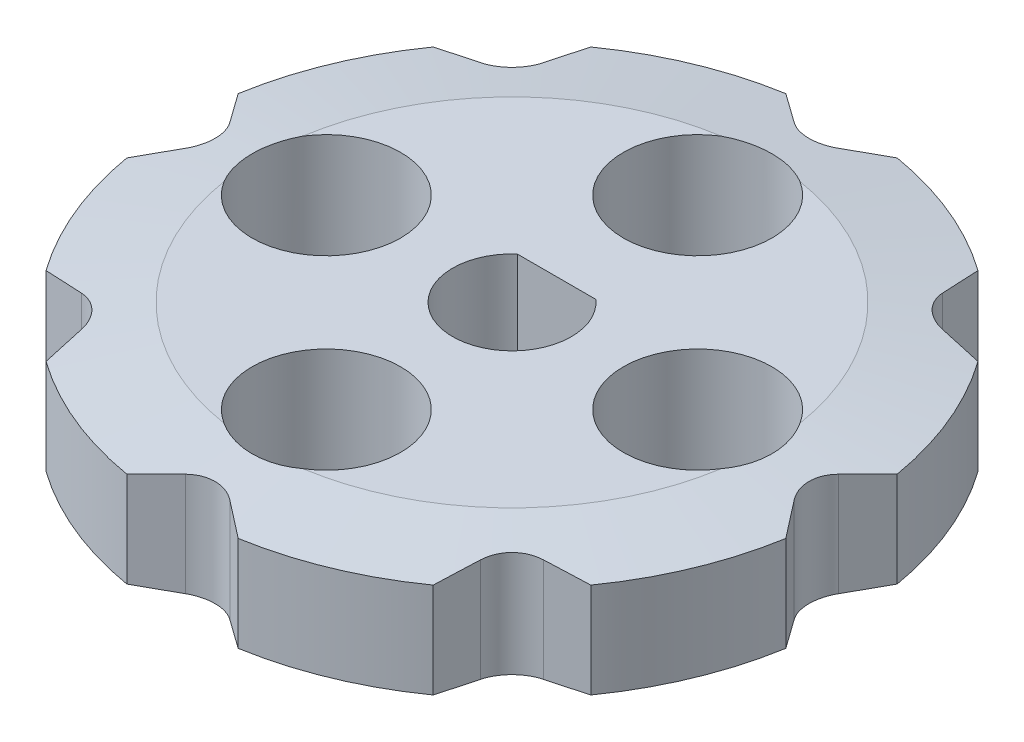
SolidWorks part; units mm, degrees
ref_plane "前视基准面" through (0, 0, 0) normal (0, 0, 1) x (1, 0, 0)
ref_plane "上视基准面" through (0, 0, 0) normal (0, 1, 0) x (1, 0, 0)
ref_plane "右视基准面" through (0, 0, 0) normal (1, 0, 0) x (0, 0, -1)
sketch "草图1" plane through (0, 0, 0) normal (0, 1, 0) x (1, 0, 0)
  line L0 (1.0583, 1.2) -> (-1.0583, 1.2)
  circle A0 centre (0, 0) radius 9
  circle A1 centre (0, 0) radius 1.6
  dimension "D1" = 3.2
  dimension "D2" = 1.2
  dimension "D3" = 18
extrude "凸台-拉伸1" add sketch "草图1" along normal blind 3.2 contours L0 A1 | A0 A1
sketch "草图4" plane through (0, 3.2, 0) normal (0, 1, 0) x (1, 0, 0)
  line L0 (-0.5995, 8.1996) -> (-1.5, 8.8741)
  line L1 (0, 9) -> (0, 0) construction
  line L2 (0.5995, 8.1996) -> (1.5, 8.8741)
  circle A0 centre (0, 0) radius 9 construction
  circle A1 centre (0, 9) radius 1
  circle A2 centre (0, 0) radius 9
  dimension "D2" = 1.5
  dimension "D1" = 2
  dimension "D3" = 1.5
extrude "切除-拉伸2" cut sketch "草图4" against normal up to next
pattern_circular "阵列(圆周)1" count 8 over 360 about axis through (0, 0, 0) along (0, 1, 0) of "切除-拉伸2"
sketch "草图3" plane through (0, 3.2, 0) normal (0, 1, 0) x (1, 0, 0)
  circle A0 centre (0, 5) radius 2
  dimension "D1" = 4
  dimension "D3" = 5
extrude "切除-拉伸1" cut sketch "草图3" against normal up to next
pattern_circular "阵列(圆周)2" count 4 over 360 about axis through (0, 0, 0) along (0, 1, 0) of "切除-拉伸1"
sketch "草图5" plane through (0, 0, 0) normal (1, 0, 0) x (0, 0, -1)
  line L0 (9.3741, 2.8284) -> (6.7788, 3.2)
  line L2 (6.2219, 3.2) -> (7.3356, 3.2) construction
  line L3 (6.7788, 3.2) -> (9.3741, 3.2)
  line L4 (8.8741, 3.2) -> (7.3356, 3.2) construction
  line L5 (9.3741, 3.2) -> (9.3741, 2.8284)
  line L6 (8.8741, 0) -> (8.8741, 3.2) construction
  line L7 (8.8741, 3.2) -> (8.8741, 2.9) construction
  dimension "D1" = 0.3
  dimension "D2" = 0.5
ref_axis "基准轴1" through (0, 3.2, 0) along (0, -1, 0)
revolve "切除-旋转1" cut sketch "草图5" angle 360 about axis through (0, 3.2, 0) along (0, -1, 0)
ref_plane "基准面1" through (0, 1.6, 0) normal (0, 1, 0) x (1, 0, 0)
mirror "镜向1" about plane through (0, 1.6, 0) normal (0, 1, 0) of "切除-旋转1"
